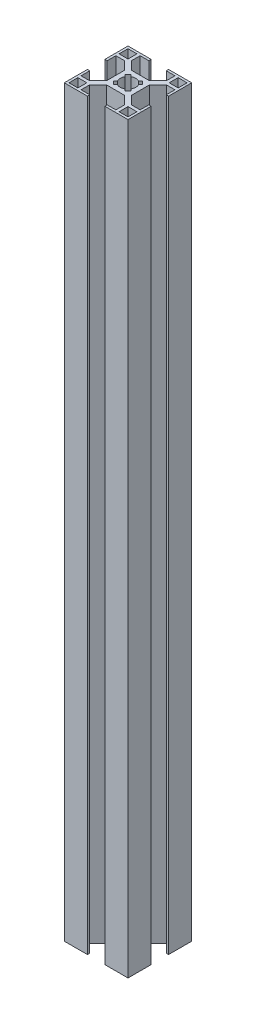
SolidWorks part; units mm, degrees
material "3.0255 (EN-AW 1350A)"
ref_plane "Alzado" through (0, 0, 0) normal (0, 0, 1) x (1, 0, 0)
ref_plane "Planta" through (0, 0, 0) normal (0, 1, 0) x (1, 0, 0)
ref_plane "Vista lateral" through (0, 0, 0) normal (1, 0, 0) x (0, 0, -1)
sketch "Croquis2" plane through (0, 0, 0) normal (0, 1, 0) x (1, 0, 0)
  line L0 (-12.6732, 23.1711) -> (-8.4732, 23.1711)
  line L1 (-37.3732, 24.2711) -> (-26.4982, 24.2711)
  line L2 (-37.3732, 24.2711) -> (-37.3732, 13.3961)
  line L3 (-37.3732, -5.7289) -> (-26.4982, -5.7289)
  line L4 (-7.3732, 24.2711) -> (-7.3732, 13.3961)
  line L5 (-30.5732, -4.6289) -> (-26.4982, -4.6289)
  line L6 (-30.5732, 23.1711) -> (-26.4982, 23.1711)
  line L7 (-36.2732, 5.1461) -> (-37.3732, 5.1461)
  line L8 (-8.4732, 23.1711) -> (-8.4732, 18.9711)
  line L9 (-36.2732, -4.6289) -> (-32.0732, -4.6289)
  line L10 (-36.2732, 23.1711) -> (-36.2732, 18.9711)
  line L11 (-36.2732, 23.1711) -> (-32.0732, 23.1711)
  line L12 (-32.0732, -0.4289) -> (-36.2732, -0.4289)
  line L15 (-8.4732, 18.9711) -> (-12.6732, 18.9711)
  line L16 (-12.6732, 23.1711) -> (-12.6732, 18.9711)
  line L17 (-32.0732, -0.4289) -> (-32.0732, -4.6289)
  line L19 (-36.2732, -0.4289) -> (-36.2732, -4.6289)
  line L21 (-32.0732, 23.1711) -> (-32.0732, 18.9711)
  line L22 (-32.0732, 18.9711) -> (-36.2732, 18.9711)
  line L24 (-8.4732, -0.4289) -> (-12.6732, -0.4289)
  line L25 (-8.4732, -0.4289) -> (-8.4732, -4.6289)
  line L26 (-8.4732, -4.6289) -> (-12.6732, -4.6289)
  line L27 (-12.6732, -0.4289) -> (-12.6732, -4.6289)
  line L28 (-26.5862, 3.3611) -> (-18.1603, 3.3611)
  line L29 (-16.4632, 13.4841) -> (-16.4632, 5.0582)
  line L30 (-26.5862, 15.1811) -> (-18.1603, 15.1811)
  line L31 (-28.2832, 13.4841) -> (-28.2832, 5.0582)
  line L32 (-28.2832, 15.1811) -> (-16.4632, 15.1811) construction
  line L33 (-28.2832, 3.3611) -> (-16.4632, 3.3611) construction
  line L34 (-7.3732, 5.1461) -> (-8.4732, 5.1461)
  line L35 (-7.3732, 13.3961) -> (-8.4732, 13.3961)
  line L36 (-26.4982, 24.2711) -> (-26.4982, 23.1711)
  line L37 (-18.2482, 24.2711) -> (-18.2482, 23.1711)
  line L38 (-36.2732, 13.3961) -> (-37.3732, 13.3961)
  line L39 (-19.1655, 11.0646) -> (-18.2482, 11.9819)
  line L40 (-36.2732, 5.1461) -> (-36.2732, 1.0711)
  line L41 (-36.2732, 23.1711) -> (-36.2732, -4.6289) construction
  line L42 (-37.3732, 5.1461) -> (-37.3732, -5.7289)
  line L43 (-37.3732, 24.2711) -> (-37.3732, -5.7289) construction
  line L44 (-18.2482, -4.6289) -> (-18.2482, -5.7289)
  line L46 (-8.4732, 5.1461) -> (-8.4732, 1.0711)
  line L47 (-8.4732, 23.1711) -> (-8.4732, -4.6289) construction
  line L48 (-7.3732, 5.1461) -> (-7.3732, -5.7289)
  line L49 (-7.3732, 24.2711) -> (-7.3732, -5.7289) construction
  line L51 (-25.084, 5.1461) -> (-24.1667, 6.0634)
  line L52 (-18.2482, -4.6289) -> (-14.1732, -4.6289)
  line L53 (-36.2732, -4.6289) -> (-8.4732, -4.6289) construction
  line L54 (-18.2482, -5.7289) -> (-7.3732, -5.7289)
  line L55 (-37.3732, -5.7289) -> (-7.3732, -5.7289) construction
  line L56 (-16.4632, 15.1811) -> (-16.4632, 3.3611) construction
  line L57 (-26.4982, 11.9819) -> (-25.5809, 11.0646)
  line L58 (-18.2482, 23.1711) -> (-14.1732, 23.1711)
  line L59 (-36.2732, 23.1711) -> (-8.4732, 23.1711) construction
  line L60 (-18.2482, 24.2711) -> (-7.3732, 24.2711)
  line L61 (-37.3732, 24.2711) -> (-7.3732, 24.2711) construction
  line L62 (-32.2703, 1.0711) -> (-36.2732, 1.0711)
  line L63 (-30.5732, 1.0711) -> (-37.7732, 1.0711) construction
  line L64 (-30.5732, 1.0711) -> (-30.5732, -6.1289) construction
  line L65 (-30.5732, -0.6259) -> (-30.5732, -4.6289)
  line L66 (-8.4732, 1.0711) -> (-12.4762, 1.0711)
  line L67 (-14.1732, -0.6259) -> (-14.1732, -4.6289)
  line L68 (-6.9732, 1.0711) -> (-6.9732, -6.1289) construction
  line L69 (-30.5732, -0.6259) -> (-26.5862, 3.3611)
  line L70 (-6.9732, 17.4711) -> (-14.1732, 17.4711) construction
  line L71 (-8.4732, 17.4711) -> (-12.4762, 17.4711)
  line L72 (-14.1732, 23.1711) -> (-14.1732, 19.1682)
  line L73 (-8.4732, 17.4711) -> (-8.4732, 13.3961)
  line L74 (-32.2703, 17.4711) -> (-36.2732, 17.4711)
  line L75 (-30.5732, 24.6711) -> (-30.5732, 17.4711) construction
  line L76 (-16.4632, 13.4841) -> (-12.4762, 17.4711)
  line L77 (-30.5732, 23.1711) -> (-30.5732, 19.1682)
  line L78 (-30.5732, -6.1289) -> (-37.7732, -6.1289) construction
  line L79 (-37.7732, 1.0711) -> (-37.7732, -6.1289) construction
  line L80 (-26.4982, -4.6289) -> (-26.4982, -5.7289)
  line L81 (-30.5732, 19.1682) -> (-26.5862, 15.1811)
  line L83 (-18.1603, 3.3611) -> (-14.1732, -0.6259)
  line L84 (-30.5732, 17.4711) -> (-37.7732, 17.4711) construction
  line L85 (-37.7732, 24.6711) -> (-37.7732, 17.4711) construction
  line L86 (-30.5732, 24.6711) -> (-37.7732, 24.6711) construction
  line L87 (-36.2732, 17.4711) -> (-36.2732, 13.3961)
  line L88 (-32.2703, 1.0711) -> (-28.2832, 5.0582)
  line L90 (-6.9732, -6.1289) -> (-14.1732, -6.1289) construction
  line L91 (-14.1732, 1.0711) -> (-14.1732, -6.1289) construction
  line L92 (-6.9732, 1.0711) -> (-14.1732, 1.0711) construction
  line L94 (-25.084, 13.3961) -> (-24.1667, 12.4788)
  line L95 (-19.1655, 7.4777) -> (-18.2482, 6.5603)
  line L96 (-20.5798, 6.0634) -> (-19.6624, 5.1461)
  line L97 (-14.1732, 24.6711) -> (-14.1732, 17.4711) construction
  line L98 (-6.9732, 24.6711) -> (-14.1732, 24.6711) construction
  line L99 (-6.9732, 24.6711) -> (-6.9732, 17.4711) construction
  line L100 (-16.4632, 5.0582) -> (-12.4762, 1.0711)
  line L101 (-26.4982, 6.5603) -> (-25.5809, 7.4777)
  line L104 (-28.2832, 15.1811) -> (-28.2832, 3.3611) construction
  line L105 (-18.1603, 15.1811) -> (-14.1732, 19.1682)
  line L106 (-32.2703, 17.4711) -> (-28.2832, 13.4841)
  line L111 (-20.5798, 12.4788) -> (-19.6624, 13.3961)
  line L114 (-26.4982, 6.5603) -> (-25.084, 5.1461)
  line L115 (-19.6624, 5.1461) -> (-18.2482, 6.5603)
  line L116 (-19.6624, 13.3961) -> (-18.2482, 11.9819)
  line L117 (-25.084, 13.3961) -> (-26.4982, 11.9819)
  line L119 (-32.0732, 23.1711) -> (-36.2732, 23.1711) construction
  line L120 (-8.4732, 23.1711) -> (-12.6732, 23.1711) construction
  line L121 (-32.0732, -4.6289) -> (-36.2732, -4.6289) construction
  line L122 (-8.4732, 23.1711) -> (-8.4732, 18.9711) construction
  line L123 (-36.2732, 23.1711) -> (-36.2732, 18.9711) construction
  arc A0 (-25.5809, 11.0646) -> (-25.5809, 7.4777) centre (-22.3732, 9.2711) ccw
  arc A1 (-20.5798, 12.4788) -> (-24.1667, 12.4788) centre (-22.3732, 9.2711) ccw
  arc A2 (-19.1655, 7.4777) -> (-19.1655, 11.0646) centre (-22.3732, 9.2711) ccw
  arc A3 (-24.1667, 6.0634) -> (-20.5798, 6.0634) centre (-22.3732, 9.2711) ccw
  dimension "D1" = 30
  dimension "D2" = 30
  dimension "D5" = 1.5
extrude "Saliente-Extruir1" add sketch "Croquis2" along normal blind 350
